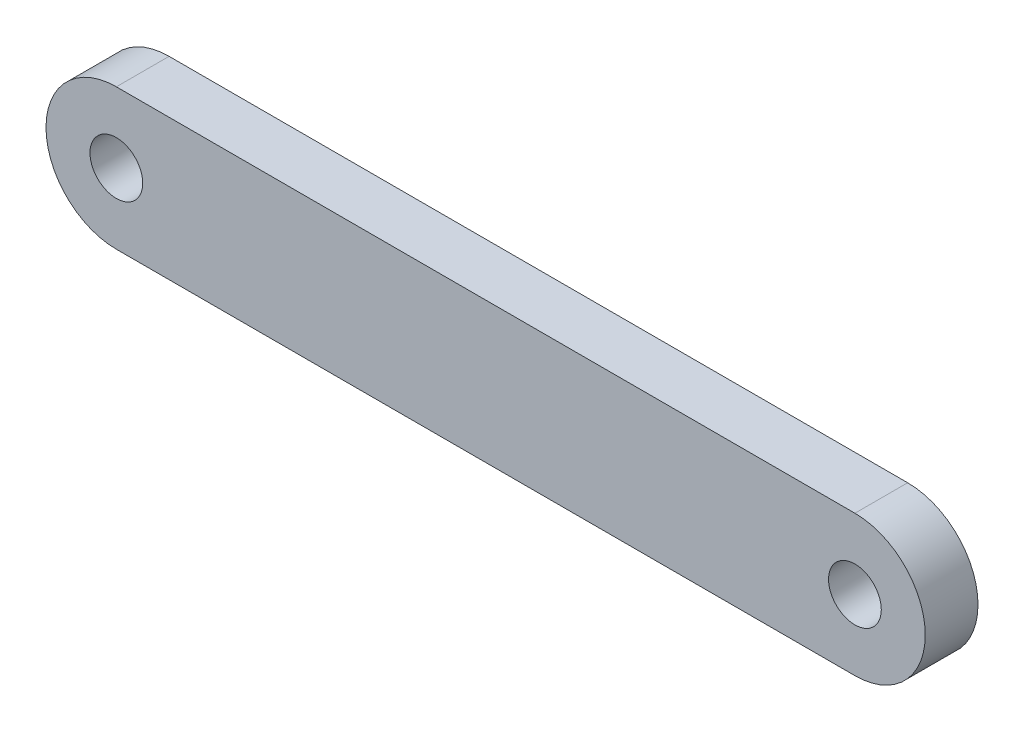
SolidWorks part; units mm, degrees
ref_plane "Front Plane" through (0, 0, 0) normal (0, 0, 1) x (1, 0, 0)
ref_plane "Top Plane" through (0, 0, 0) normal (0, 1, 0) x (1, 0, 0)
ref_plane "Right Plane" through (0, 0, 0) normal (1, 0, 0) x (0, 0, -1)
sketch "Sketch1" plane through (0, 0, 0) normal (0, 0, 1) x (1, 0, 0)
  line L0 (-125, 0) -> (125, 0) construction
  line L1 (0, -26.8125) -> (0, 26.8125) construction
  line L3 (-105, -20) -> (105, -20)
  line L5 (-105, 20) -> (105, 20)
  arc A0 (-105, 20) -> (-105, -20) centre (-105, 0) ccw
  arc A1 (105, 20) -> (105, -20) centre (105, 0) cw
  point P0 (0, 0)
  point P4 (0, 0)
  point P8 (0, 0)
  dimension "D1" = 125
  dimension "D2" = 210
  dimension "D3" = 20
extrude "Boss-Extrude1" add sketch "Sketch1" along normal blind 15
ref_plane "Plane1" through (-105, 0, 0) normal (1, 0, 0) x (0, 0, -1)
sketch "Sketch4" plane through (0, 0, 15) normal (0, 0, 1) x (1, 0, 0)
  circle A0 centre (105, 0) radius 7.5
  circle A1 centre (52.1657, 0) radius 7.5401
  dimension "D2" = 15
  dimension "D1" = 105
extrude "Cut-Extrude1" cut sketch "Sketch4" against normal through all contours A0
mirror "Mirror1" about plane through (0, 0, 0) normal (1, 0, 0) of "Cut-Extrude1"
